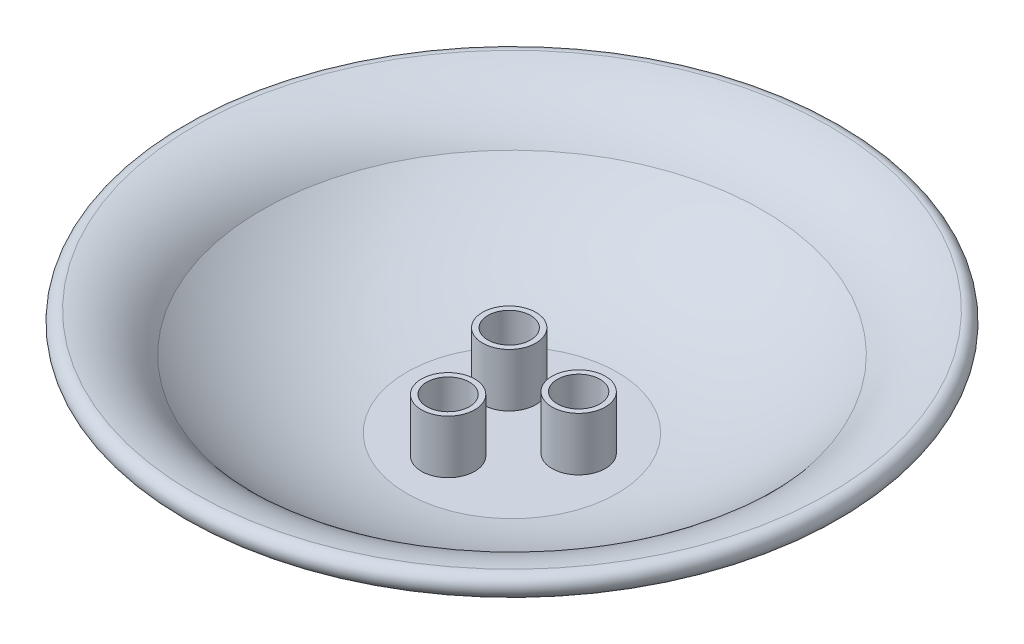
SolidWorks part; units mm, degrees
ref_plane "Front Plane" through (0, 0, 0) normal (0, 0, 1) x (1, 0, 0)
ref_plane "Top Plane" through (0, 0, 0) normal (0, 1, 0) x (1, 0, 0)
ref_plane "Right Plane" through (0, 0, 0) normal (1, 0, 0) x (0, 0, -1)
sketch "Sketch1" plane through (0, 0, 0) normal (0, 0, 1) x (1, 0, 0)
  line L3 (3.1193, -4.8165) -> (13.1193, -4.8165)
  line L6 (3.2579, -2.8165) -> (13.1193, -2.8165)
  line L7 (13.1193, -2.8165) -> (13.1193, -4.8165)
  arc A0 (-16.8807, 5.1835) -> (-11.8807, 2.1835) centre (-17.5986, -1.6796) cw
  arc A1 (3.1193, -4.8165) -> (-11.8807, 2.1835) centre (6.9048, 22.8668) cw
  arc A2 (-16.6727, 7.1726) -> (-10.3722, 3.5164) centre (-17.5986, -1.6796) cw
  arc A3 (3.2579, -2.8165) -> (-10.3722, 3.5164) centre (6.9048, 22.8668) cw
  arc A4 (-16.8807, 5.1835) -> (-16.6727, 7.1726) centre (-16.7767, 6.1781) cw
  dimension "D1" = 2
  dimension "D5" = 10
revolve "Revolve1" add sketch "Sketch1" angle 360 about L7
sketch "Sketch2" plane through (0, -2.8165, 0) normal (0, 1, 0) x (1, 0, 0)
  circle A0 centre (9.4558, 3.4028) radius 2.5
  circle A1 centre (13.1193, 0) radius 9.8613 construction
  circle A2 centre (9.4558, 3.4028) radius 2
  circle A3 centre (17.8979, 1.4713) radius 2.5
  circle A4 centre (17.8979, 1.4713) radius 2
  circle A5 centre (12.0041, -4.8741) radius 2.5
  circle A6 centre (12.0041, -4.8741) radius 2
  dimension "D1" = 5
  dimension "D2" = 5
  dimension "D3" = 4
  dimension "D4" = 3
extrude "Boss-Extrude2" add sketch "Sketch2" along normal blind 5
